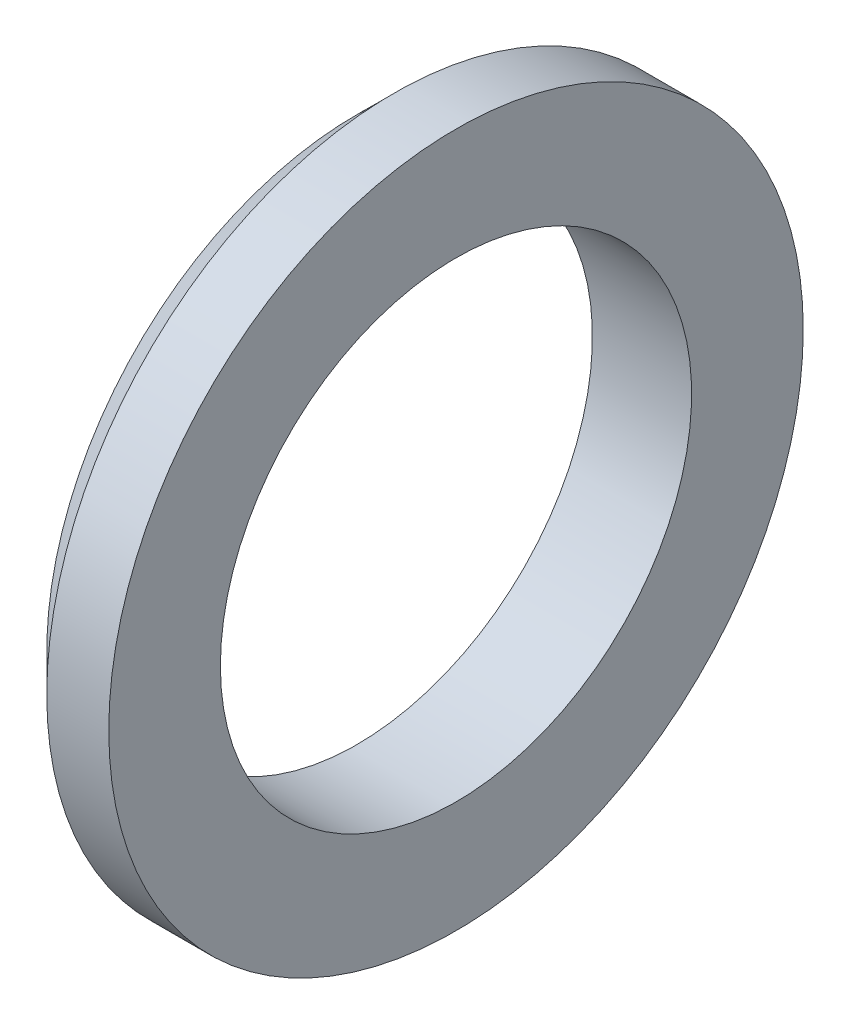
SolidWorks part; units mm, degrees
material "Q235A"
ref_plane "前视基准面" through (0, 0, 0) normal (0, 0, 1) x (1, 0, 0)
ref_plane "上视基准面" through (0, 0, 0) normal (0, 1, 0) x (1, 0, 0)
ref_plane "右视基准面" through (0, 0, 0) normal (1, 0, 0) x (0, 0, -1)
sketch "草图1" plane through (0, 0, 0) normal (0, 0, 1) x (1, 0, 0)
  line L0 (-16.9833, 0) -> (14.9473, 0) construction
  line L1 (0, 9.5) -> (0, 14)
  line L2 (0, 14) -> (-4, 14)
  line L3 (-4, 14) -> (-4, 9.5)
  line L4 (-4, 9.5) -> (0, 9.5)
  line L5 (0, 9.5) -> (0, 0) construction
  dimension "D1" = 19
  dimension "D2" = 28
  dimension "D3" = 4
revolve "旋转1" add sketch "草图1" angle 360 about L0
chamfer "倒角1" distance 1.5 angle 45 1 edges at (-4, 0, 14)
